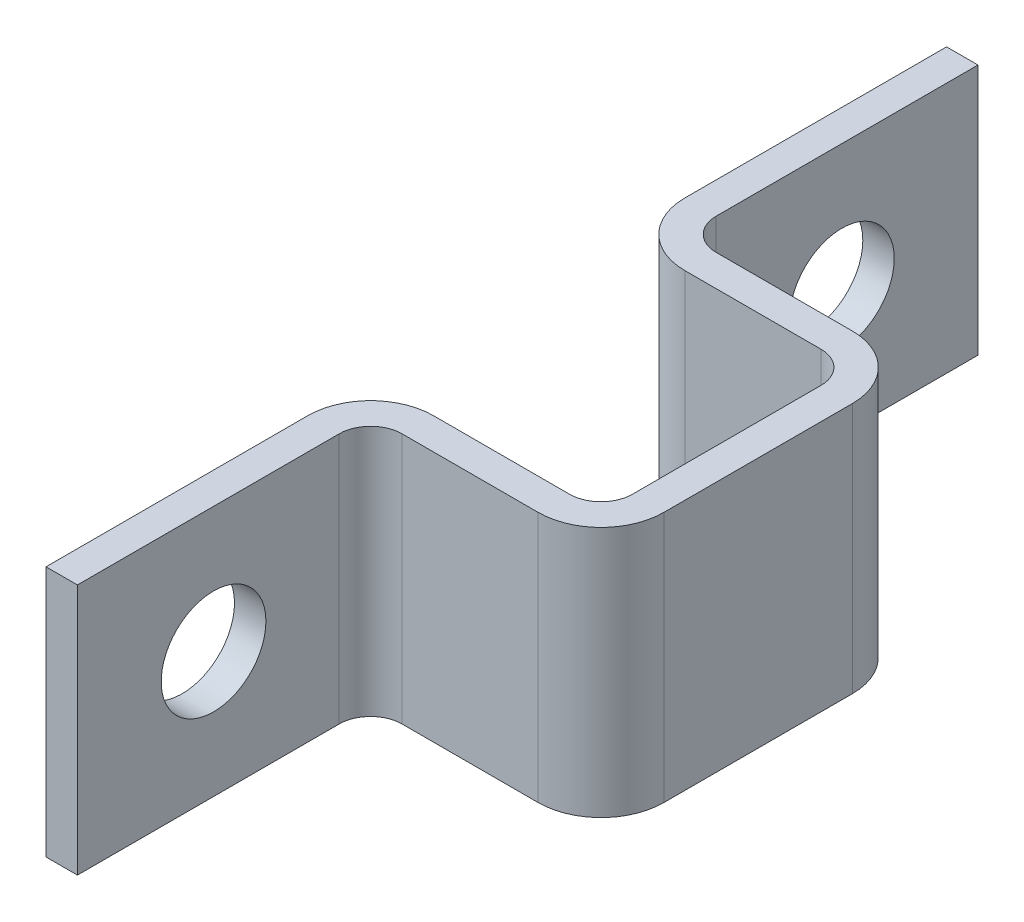
SolidWorks part; units mm, degrees
ref_plane "Front Plane" through (0, 0, 0) normal (0, 0, 1) x (1, 0, 0)
ref_plane "Top Plane" through (0, 0, 0) normal (0, 1, 0) x (1, 0, 0)
ref_plane "Right Plane" through (0, 0, 0) normal (1, 0, 0) x (0, 0, -1)
sketch "Sketch1" plane through (0, 0, 0) normal (0, 1, 0) x (1, 0, 0)
  line L0 (0, 21.5) -> (0, 9)
  line L2 (3, 6) -> (9.5, 6)
  line L3 (11, 4.5) -> (11, -4.5)
  line L4 (9.5, -6) -> (3, -6)
  line L5 (0, -9) -> (0, -21.5)
  arc A1 (0, 9) -> (3, 6) centre (3, 9) ccw
  arc A2 (3, -6) -> (0, -9) centre (3, -9) ccw
  arc A3 (9.5, 6) -> (11, 4.5) centre (9.5, 4.5) cw
  arc A4 (9.5, -6) -> (11, -4.5) centre (9.5, -4.5) ccw
  point P8 (11, 0)
  dimension "FIX_1" = 3
  dimension "FIX_2" = 1.5
  dimension "MSM_16" = 43
  dimension "MSM_17" = 12
  dimension "MSM_18" = 11
extrude "Extrude-Thin1" add sketch "Sketch1" along normal blind 12 thin thin type one direction reverse wall 1.5
sketch "Sketch2" plane through (0, 0, 0) normal (1, 0, 0) x (0, 0, -1)
  line L0 (21.5, 12) -> (21.5, 0) construction
  line L1 (21.5, 12) -> (21.5, 0) construction
  circle A0 centre (-15, 6) radius 2.5
  circle A1 centre (15, 6) radius 2.5
  point P7 (21.5, 6)
  dimension "MSM_21" = 5
  dimension "MSM_20" = 30
  dimension "FIX_4" = 15
extrude "Cut-Extrude1" cut sketch "Sketch2" along normal through all
equation "\"FIX_4@Sketch2\" = \"MSM_20@Sketch2\" / 2"
